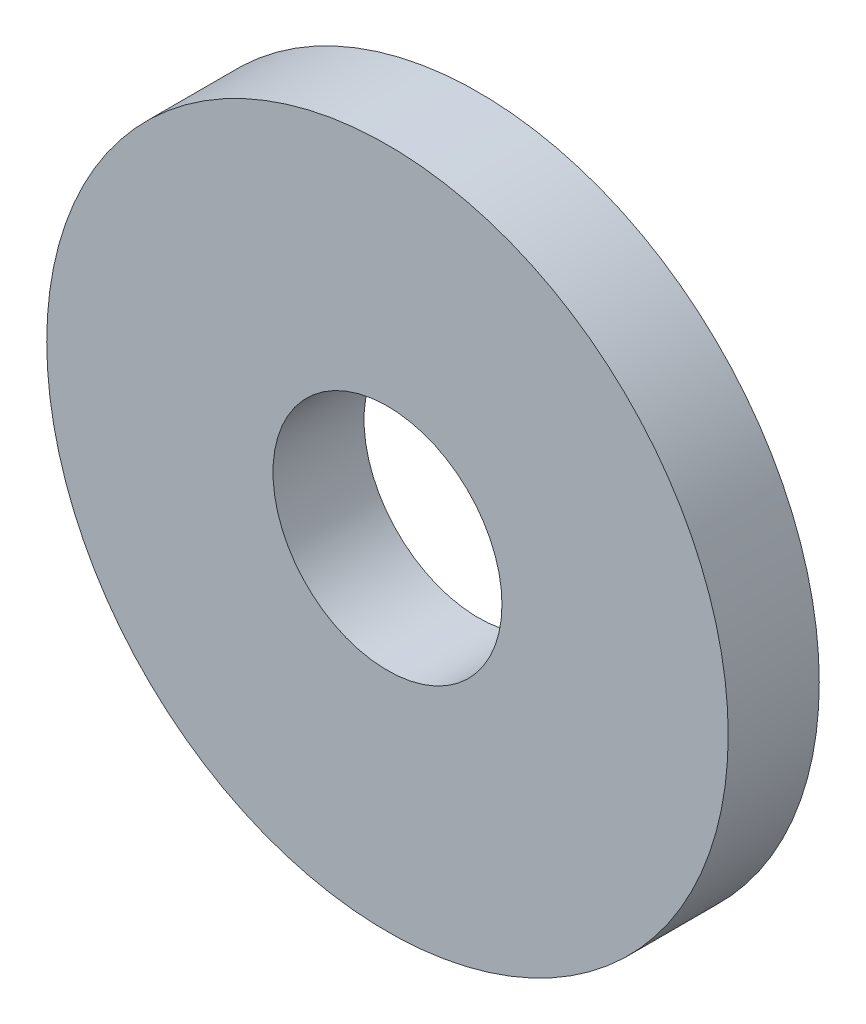
SolidWorks part; units mm, degrees
ref_plane "前视基准面" through (0, 0, 0) normal (0, 0, 1) x (1, 0, 0)
ref_plane "上视基准面" through (0, 0, 0) normal (0, 1, 0) x (1, 0, 0)
ref_plane "右视基准面" through (0, 0, 0) normal (1, 0, 0) x (0, 0, -1)
sketch "草图1" plane through (0, 0, 0) normal (0, 0, 1) x (1, 0, 0)
  circle A0 centre (0, 0) radius 14.97
  circle A1 centre (0, 0) radius 5.03
  dimension "D1" = 29.94
  dimension "D2" = 10.06
extrude "凸台-拉伸1" add sketch "草图1" along normal blind 4 contours A0
